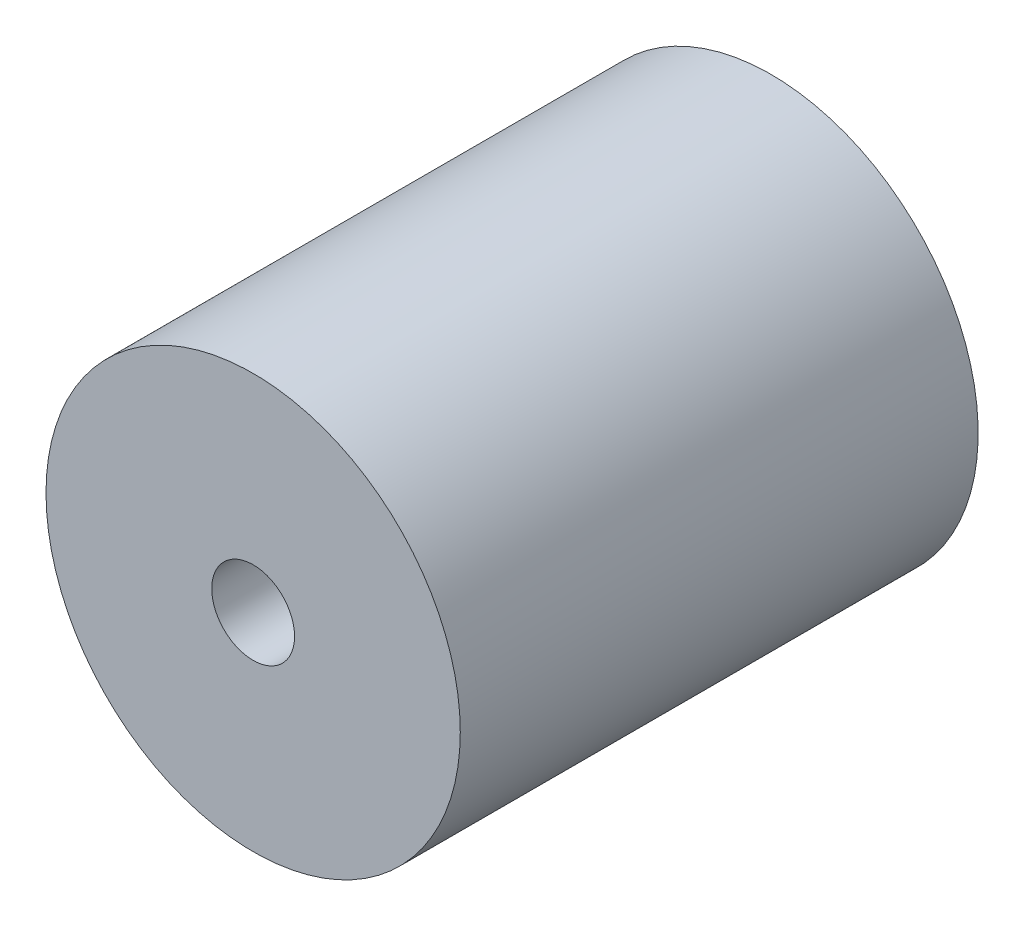
SolidWorks part; units mm, degrees
ref_plane "Front Plane" through (0, 0, 0) normal (0, 0, 1) x (1, 0, 0)
ref_plane "Top Plane" through (0, 0, 0) normal (0, 1, 0) x (1, 0, 0)
ref_plane "Right Plane" through (0, 0, 0) normal (1, 0, 0) x (0, 0, -1)
sketch "Sketch1" plane through (0, 0, 0) normal (0, 0, 1) x (1, 0, 0)
  circle A0 centre (0, 0) radius 2
  circle A1 centre (0, 0) radius 10
  dimension "D1" = 4
  dimension "D2" = 20
extrude "Boss-Extrude1" add sketch "Sketch1" along normal blind 10
sketch "Sketch4" plane through (0, 0, 0) normal (0, 0, -1) x (-1, 0, 0)
  circle A0 centre (0, 0) radius 10
extrude "Boss-Extrude3" add sketch "Sketch4" along normal blind 5
sketch "Sketch5" plane through (0, 0, -5) normal (0, 0, -1) x (-1, 0, 0)
  circle A0 centre (0, 0) radius 10
  circle A1 centre (0, 0) radius 2
  dimension "D1" = 4
  dimension "D2" = 20
extrude "Boss-Extrude4" add sketch "Sketch5" along normal blind 10
